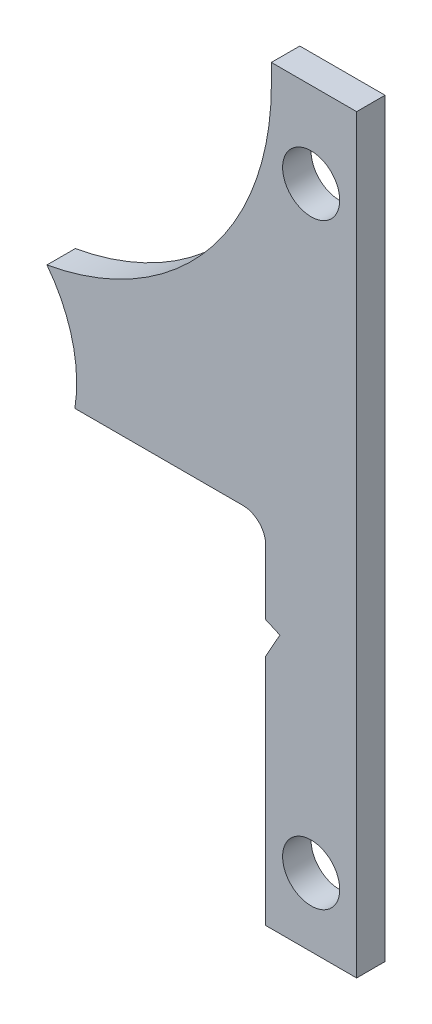
SolidWorks part; units mm, degrees
ref_plane "Front Plane" through (0, 0, 0) normal (0, 0, 1) x (1, 0, 0)
ref_plane "Top Plane" through (0, 0, 0) normal (0, 1, 0) x (1, 0, 0)
ref_plane "Right Plane" through (0, 0, 0) normal (1, 0, 0) x (0, 0, -1)
sketch "Sketch1" plane through (0, 0, 0) normal (0, 0, 1) x (1, 0, 0)
  line L0 (-49.5702, -4) -> (-20, -4)
  line L1 (0, 66) -> (-15, 66)
  line L2 (0, 66) -> (0, -66)
  line L3 (0, -66) -> (-16, -66)
  line L4 (-15, 66) -> (-15, 62.56)
  line L5 (-16, -19.4031) -> (-13.5007, -20.5015)
  line L6 (-16, -24.97) -> (-16, -66)
  line L7 (-16, -19.4031) -> (-16, -8)
  line L9 (-13.5007, -20.5015) -> (-16, -24.97)
  arc A3 (-54.4813, 15.4056) -> (-15, 62.56) centre (-62.9, 62.56) ccw
  arc A4 (-49.5702, -4) -> (-54.4813, 15.4056) centre (-74.52, 0.01) ccw
  arc A5 (-16, -8) -> (-20, -4) centre (-20, -8) ccw
  dimension "D3" = 8
  dimension "D6" = 3.44
  dimension "D9" = 5.12
  dimension "D15" = 50.54
  dimension "D1" = 15
  dimension "D2" = 132
  dimension "D7" = 62.9
  dimension "D8" = 5.5669
  dimension "D10" = 41.03
  dimension "D11" = 16
  dimension "D12" = 3.44
  dimension "D13" = 2.73
  dimension "D14" = 66
  dimension "D16" = 66.01
  dimension "D17" = 74.52
  dimension "D18" = 62
extrude "Boss-Extrude1" add sketch "Sketch1" along normal mid plane 5
sketch "Sketch2" plane through (0, 0, 2.5) normal (0, 0, 1) x (1, 0, 0)
  line L0 (0, -2.75) -> (0, 2.75) construction
  line L1 (0, 66) -> (-15, 66) construction
  circle A0 centre (-8, 51) radius 5.025
  circle A1 centre (-8, -54) radius 5.025
  point P8 (0, 0)
  point P9 (0, 0)
  dimension "D1" = 10.05
  dimension "D2" = 8
  dimension "D3" = 15
  dimension "D4" = 105
extrude "Cut-Extrude1" cut sketch "Sketch2" against normal through all
